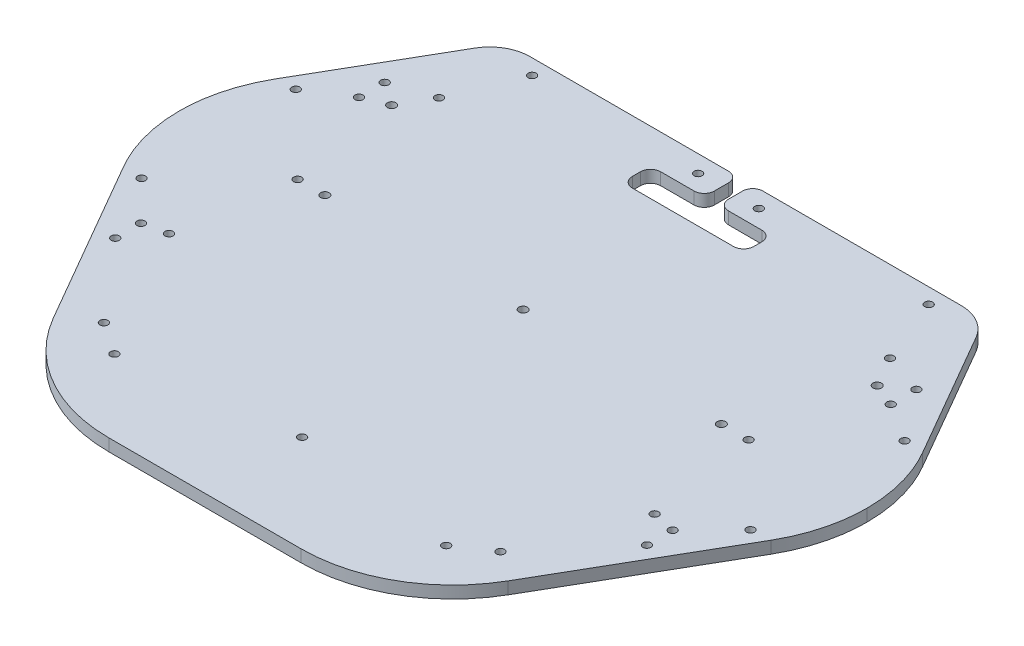
SolidWorks part; units mm, degrees
ref_plane "Front Plane" through (0, 0, 0) normal (0, 0, 1) x (1, 0, 0)
ref_plane "Top Plane" through (0, 0, 0) normal (0, 1, 0) x (1, 0, 0)
ref_plane "Right Plane" through (0, 0, 0) normal (1, 0, 0) x (0, 0, -1)
ref_plane "Plane1" through (0, 6, 0) normal (0, 1, 0) x (1, 0, 0)
sketch "Sketch1" plane through (0, 6, 0) normal (0, 1, 0) x (1, 0, 0)
  line L0 (118.094, 110) -> (-118.094, 110)
  line L1 (-118.094, 110) -> (-159.9519, 37.5)
  line L2 (-159.9519, -37.5) -> (-90.8013, -157.2724)
  line L3 (-90.8013, -157.2724) -> (90.8013, -157.2724)
  line L4 (90.8013, -157.2724) -> (159.9519, -37.5)
  line L5 (159.9519, 37.5) -> (118.094, 110)
  spline S0 degree 3 poles (-159.9519, 37.5) (-162.0898, 33.7968) (-165.8426, 25.7861) (-169.2445, 13.0899) (-169.9999, 4.2761) (-170, 0) knots 5.759587 5.759587 5.759587 5.759587 5.930629 6.112143 6.283185 6.283185 6.283185 6.283185
  spline S1 degree 3 poles (-170, 0) (-169.9999, -4.2761) (-169.2445, -13.0899) (-165.8426, -25.7861) (-162.0898, -33.7968) (-159.9519, -37.5) knots 0 0 0 0 0.171042 0.352557 0.523599 0.523599 0.523599 0.523599
  spline S2 degree 3 poles (159.9519, -37.5) (162.0898, -33.7968) (165.8426, -25.7861) (169.2445, -13.0899) (169.9999, -4.2761) (170, 0) knots 2.617994 2.617994 2.617994 2.617994 2.789036 2.97055 3.141593 3.141593 3.141593 3.141593
  spline S3 degree 3 poles (170, 0) (169.9999, 4.276) (169.2445, 13.0899) (165.8426, 25.7861) (162.0898, 33.7968) (159.9519, 37.5) knots 3.141593 3.141593 3.141593 3.141593 3.312635 3.494149 3.665191 3.665191 3.665191 3.665191
extrude "Boss-Extrude1" add sketch "Sketch1" against normal blind 6
sketch "Sketch2" plane through (0, 0, 0) normal (0, -1, 0) x (1, 0, 0)
  line L0 (3.5, -110) -> (3.5, -93)
  line L1 (3.5, -93) -> (30, -93)
  line L2 (30, -93) -> (30, -79)
  line L3 (30, -79) -> (-30, -79)
  line L4 (-30, -79) -> (-30, -93)
  line L5 (-30, -93) -> (-3.5, -93)
  line L6 (-3.5, -93) -> (-3.5, -110)
  line L7 (-3.5, -110) -> (3.5, -110)
extrude "Cut-Extrude1" cut sketch "Sketch2" against normal through all
hole_wizard "M3.5 Clearance Hole1" positions "Sketch4" profile "Sketch3" hole size "M3.5" standard "ANSI Metric"
sketch "Sketch4" plane through (0, 0, 0) normal (0, -1, 0) x (-1, 0, 0)
  point P0 (0, -0.0015)
  point P1 (-97.9932, 0.0015)
  point P2 (97.9932, 0.0015)
  point P3 (120, 55.0015)
  point P4 (-120, 55.0015)
sketch "Sketch3" plane through (0, 0, 0.0015) normal (1, 0, 0) x (0, 0, -1)
  line L0 (0, 0) -> (0, 6.0001)
  line L1 (0, 6.0001) -> (2.0999, 6.0001)
  line L2 (2.0999, 6.0001) -> (2.0999, 0)
  line L5 (2.0999, 0) -> (0, 0)
  line L11 (0, -6.35) -> (0, 107.95) construction
  dimension "Thru Hole Dia." = 4.1998
  dimension "Thru Hole Depth" = 6.0001
hole_wizard "M3.5 Clearance Hole2" positions "Sketch6" profile "Sketch5" hole size "M3.5" standard "ANSI Metric"
sketch "Sketch6" plane through (0, 0, 0) normal (0, -1, 0) x (-1, 0, 0)
  point P0 (98, 102.4382)
  point P1 (0, -109.22)
  point P2 (98, -109.22)
  point P3 (-98, -109.22)
  point P4 (111.4552, 69.85)
  point P5 (111.4552, 0)
  point P6 (-111.4552, 69.85)
  point P7 (-111.4552, 0)
  point P8 (-120, -55)
  point P9 (120, -55)
  point P10 (131.4, 50.3)
  point P11 (-131.4, 50.3)
  point P12 (131.4, -70.2)
  point P13 (-131.4, -70.2)
  point P14 (131.4, 63)
  point P15 (-131.4, 63)
  point P16 (131.4, -57.5)
  point P17 (-131.4, -57.5)
  point P18 (15, 101.5)
  point P19 (-98, 102.4382)
  point P20 (-15, 101.5)
  point P21 (150.47, 38.1)
  point P22 (150.47, -38.1)
  point P23 (-150.47, 38.1)
  point P24 (-150.47, -38.1)
  point P25 (-82, -120)
  point P26 (82, -120)
sketch "Sketch5" plane through (-98, 0, -102.4382) normal (1, 0, 0) x (0, 0, -1)
  line L0 (0, 0) -> (0, 6.0001)
  line L1 (0, 6.0001) -> (1.9748, 6.0001)
  line L2 (1.9748, 6.0001) -> (1.9748, 0)
  line L5 (1.9748, 0) -> (0, 0)
  line L11 (0, -6.35) -> (0, 107.95) construction
  dimension "Thru Hole Dia." = 3.9496
  dimension "Thru Hole Depth" = 6.0001
fillet "Fillet1" radius 5.0247 8 edges at (-30, 3, -79) (30, 3, -79) (-30, 3, -93) (-3.5, 3, -93) (30, 3, -93) (3.5, 3, -93)
fillet "Fillet2" radius 19.9245 2 edges at (118.094, 3, -110) (-118.094, 3, -110)
fillet "Fillet3" radius 74.9585 2 edges at (-90.8013, 3, 157.2724) (90.8013, 3, 157.2724)
